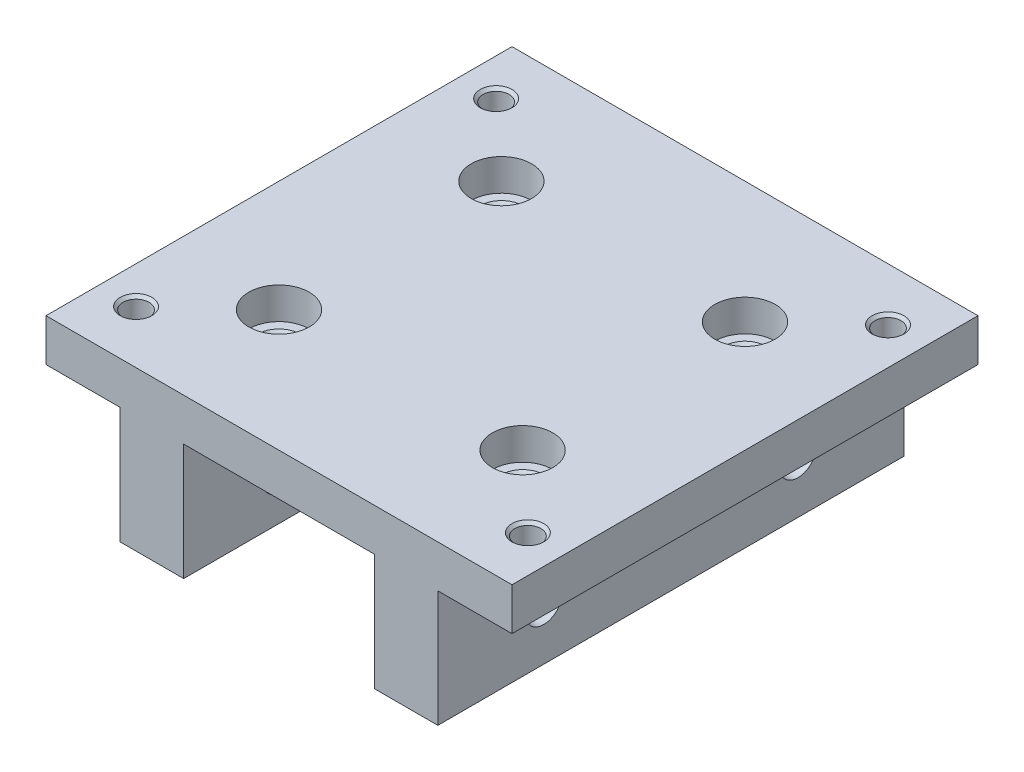
SolidWorks part; units mm, degrees
ref_plane "Front Plane" through (0, 0, 0) normal (0, 0, 1) x (1, 0, 0)
ref_plane "Top Plane" through (0, 0, 0) normal (0, 1, 0) x (1, 0, 0)
ref_plane "Right Plane" through (0, 0, 0) normal (1, 0, 0) x (0, 0, -1)
ref_plane "Plane1" through (0, 0, 0) normal (0, 0, 1) x (1, 0, 0)
sketch "Sketch1" plane through (0, 0, 0) normal (0, 0, 1) x (1, 0, 0)
  line L0 (-22, 15) -> (-22, 11)
  line L1 (-22, 11) -> (-15, 11)
  line L2 (-15, 11) -> (-15, 0)
  line L3 (-15, 0) -> (-9, 0)
  line L4 (-9, 0) -> (-9, 11)
  line L5 (-9, 11) -> (9, 11)
  line L6 (9, 11) -> (9, 0)
  line L7 (9, 0) -> (15, 0)
  line L8 (15, 0) -> (15, 11)
  line L9 (15, 11) -> (22, 11)
  line L10 (22, 11) -> (22, 15)
  line L11 (22, 15) -> (-22, 15)
extrude "Boss-Extrude1" add sketch "Sketch1" along normal blind 44
ref_plane "Plane2" through (0, 0, 5) normal (0, 0, 1) x (1, 0, 0)
sketch "Sketch2" plane through (0, 0, 5) normal (0, 0, 1) x (1, 0, 0)
  line L0 (18.5, 15) -> (20, 15)
  line L1 (20, 15) -> (19.7295, 14.7295)
  line L2 (19.7295, 14.7295) -> (19.7295, 11.2705)
  line L3 (19.7295, 11.2705) -> (20, 11)
  line L4 (20, 11) -> (18.5, 11)
  line L5 (18.5, 11) -> (18.5, 15)
  line L6 (18.5, 11) -> (18.5, 15) construction
revolve "Cut-Revolve1" cut sketch "Sketch2" angle 360 about L6
ref_plane "Plane3" through (0, 0, 39) normal (0, 0, 1) x (1, 0, 0)
sketch "Sketch3" plane through (0, 0, 39) normal (0, 0, 1) x (1, 0, 0)
  line L0 (18.5, 15) -> (20, 15)
  line L1 (20, 15) -> (19.7295, 14.7295)
  line L2 (19.7295, 14.7295) -> (19.7295, 11.2705)
  line L3 (19.7295, 11.2705) -> (20, 11)
  line L4 (20, 11) -> (18.5, 11)
  line L5 (18.5, 11) -> (18.5, 15)
  line L6 (18.5, 11) -> (18.5, 15) construction
revolve "Cut-Revolve2" cut sketch "Sketch3" angle 360 about L6
ref_plane "Plane4" through (0, 0, 10) normal (0, 0, 1) x (1, 0, 0)
sketch "Sketch4" plane through (0, 0, 10) normal (0, 0, 1) x (1, 0, 0)
  line L0 (-10.07, 1.95) -> (-10.07, 8.05)
  line L1 (-10.07, -50) -> (-10.07, 50) construction
  arc A0 (-10.07, 8.05) -> (-10.07, 1.95) centre (-10.07, 5) cw
revolve "Revolve1" add sketch "Sketch4" angle 360 about L1
ref_plane "Plane5" through (0, 0, 34) normal (0, 0, 1) x (1, 0, 0)
sketch "Sketch5" plane through (0, 0, 34) normal (0, 0, 1) x (1, 0, 0)
  line L0 (-10.07, 1.95) -> (-10.07, 8.05)
  line L1 (-10.07, -50) -> (-10.07, 50) construction
  arc A0 (-10.07, 8.05) -> (-10.07, 1.95) centre (-10.07, 5) cw
revolve "Revolve2" add sketch "Sketch5" angle 360 about L1
ref_plane "Plane6" through (0, 0, 34) normal (0, 0, 1) x (1, 0, 0)
sketch "Sketch6" plane through (0, 0, 34) normal (0, 0, 1) x (1, 0, 0)
  line L0 (10.07, 8.05) -> (10.07, 1.95)
  line L1 (10.07, 50) -> (10.07, -50) construction
  arc A0 (10.07, 1.95) -> (10.07, 8.05) centre (10.07, 5) cw
revolve "Revolve3" add sketch "Sketch6" angle 360 about L1
ref_plane "Plane7" through (0, 0, 10) normal (0, 0, 1) x (1, 0, 0)
sketch "Sketch7" plane through (0, 0, 10) normal (0, 0, 1) x (1, 0, 0)
  line L0 (10.07, 8.05) -> (10.07, 1.95)
  line L1 (10.07, 50) -> (10.07, -50) construction
  arc A0 (10.07, 1.95) -> (10.07, 8.05) centre (10.07, 5) cw
revolve "Revolve4" add sketch "Sketch7" angle 360 about L1
ref_plane "Plane8" through (20.5, 0, 0) normal (1, 0, 0) x (0, 0, -1)
sketch "Sketch8" plane through (20.5, 0, 0) normal (1, 0, 0) x (0, 0, -1)
  circle A0 centre (-10, 5) radius 1.75
extrude "Cut-Extrude1" cut sketch "Sketch8" against normal blind 7
ref_plane "Plane9" through (20.5, 0, 0) normal (1, 0, 0) x (0, 0, -1)
sketch "Sketch9" plane through (20.5, 0, 0) normal (1, 0, 0) x (0, 0, -1)
  circle A0 centre (-34, 5) radius 1.75
extrude "Cut-Extrude2" cut sketch "Sketch9" against normal blind 7
ref_plane "Plane10" through (-20.5, 0, 0) normal (1, 0, 0) x (0, 0, -1)
sketch "Sketch10" plane through (-20.5, 0, 0) normal (1, 0, 0) x (0, 0, -1)
  circle A0 centre (-10, 5) radius 1.75
extrude "Cut-Extrude3" cut sketch "Sketch10" along normal blind 7
ref_plane "Plane11" through (-20.5, 0, 0) normal (1, 0, 0) x (0, 0, -1)
sketch "Sketch11" plane through (-20.5, 0, 0) normal (1, 0, 0) x (0, 0, -1)
  circle A0 centre (-34, 5) radius 1.75
extrude "Cut-Extrude4" cut sketch "Sketch11" along normal blind 7
ref_plane "Plane12" through (0, 0, 5) normal (0, 0, 1) x (1, 0, 0)
sketch "Sketch12" plane through (0, 0, 5) normal (0, 0, 1) x (1, 0, 0)
  line L0 (-18.5, 15) -> (-17, 15)
  line L1 (-17, 15) -> (-17.2705, 14.7295)
  line L2 (-17.2705, 14.7295) -> (-17.2705, 11.2705)
  line L3 (-17.2705, 11.2705) -> (-17, 11)
  line L4 (-17, 11) -> (-18.5, 11)
  line L5 (-18.5, 11) -> (-18.5, 15)
  line L6 (-18.5, 11) -> (-18.5, 15) construction
revolve "Cut-Revolve3" cut sketch "Sketch12" angle 360 about L6
ref_plane "Plane13" through (0, 0, 39) normal (0, 0, 1) x (1, 0, 0)
sketch "Sketch13" plane through (0, 0, 39) normal (0, 0, 1) x (1, 0, 0)
  line L0 (-18.5, 15) -> (-17, 15)
  line L1 (-17, 15) -> (-17.2705, 14.7295)
  line L2 (-17.2705, 14.7295) -> (-17.2705, 11.2705)
  line L3 (-17.2705, 11.2705) -> (-17, 11)
  line L4 (-17, 11) -> (-18.5, 11)
  line L5 (-18.5, 11) -> (-18.5, 15)
  line L6 (-18.5, 11) -> (-18.5, 15) construction
revolve "Cut-Revolve4" cut sketch "Sketch13" angle 360 about L6
ref_plane "Plane14" through (11.5, 0, 0) normal (1, 0, 0) x (0, 0, -1)
sketch "Sketch14" plane through (11.5, 0, 0) normal (1, 0, 0) x (0, 0, -1)
  line L0 (-11.5, 3.8641) -> (-13.121, 4.8)
  line L1 (-13.121, 4.8) -> (-13.121, 11.621)
  line L2 (-13.121, 11.621) -> (-13.5, 12)
  line L3 (-13.5, 12) -> (-14.35, 12)
  line L4 (-14.35, 12) -> (-14.35, 15)
  line L5 (-14.35, 15) -> (-11.5, 15)
  line L6 (-11.5, 15) -> (-11.5, 3.8641)
  line L7 (-11.5, 15) -> (-11.5, 3.8641) construction
revolve "Cut-Revolve5" cut sketch "Sketch14" angle 360 about L7
ref_plane "Plane15" through (11.5, 0, 0) normal (1, 0, 0) x (0, 0, -1)
sketch "Sketch15" plane through (11.5, 0, 0) normal (1, 0, 0) x (0, 0, -1)
  line L0 (-32.5, 15) -> (-29.65, 15)
  line L1 (-29.65, 15) -> (-29.65, 12)
  line L2 (-29.65, 12) -> (-30.5, 12)
  line L3 (-30.5, 12) -> (-30.879, 11.621)
  line L4 (-30.879, 11.621) -> (-30.879, 4.8)
  line L5 (-30.879, 4.8) -> (-32.5, 3.8641)
  line L6 (-32.5, 3.8641) -> (-32.5, 15)
  line L7 (-32.5, 3.8641) -> (-32.5, 15) construction
revolve "Cut-Revolve6" cut sketch "Sketch15" angle 360 about L7
ref_plane "Plane16" through (-11.5, 0, 0) normal (1, 0, 0) x (0, 0, -1)
sketch "Sketch16" plane through (-11.5, 0, 0) normal (1, 0, 0) x (0, 0, -1)
  line L0 (-11.5, 3.8641) -> (-13.121, 4.8)
  line L1 (-13.121, 4.8) -> (-13.121, 11.621)
  line L2 (-13.121, 11.621) -> (-13.5, 12)
  line L3 (-13.5, 12) -> (-14.35, 12)
  line L4 (-14.35, 12) -> (-14.35, 15)
  line L5 (-14.35, 15) -> (-11.5, 15)
  line L6 (-11.5, 15) -> (-11.5, 3.8641)
  line L7 (-11.5, 15) -> (-11.5, 3.8641) construction
revolve "Cut-Revolve7" cut sketch "Sketch16" angle 360 about L7
ref_plane "Plane17" through (-11.5, 0, 0) normal (1, 0, 0) x (0, 0, -1)
sketch "Sketch17" plane through (-11.5, 0, 0) normal (1, 0, 0) x (0, 0, -1)
  line L0 (-32.5, 15) -> (-29.65, 15)
  line L1 (-29.65, 15) -> (-29.65, 12)
  line L2 (-29.65, 12) -> (-30.5, 12)
  line L3 (-30.5, 12) -> (-30.879, 11.621)
  line L4 (-30.879, 11.621) -> (-30.879, 4.8)
  line L5 (-30.879, 4.8) -> (-32.5, 3.8641)
  line L6 (-32.5, 3.8641) -> (-32.5, 15)
  line L7 (-32.5, 3.8641) -> (-32.5, 15) construction
revolve "Cut-Revolve8" cut sketch "Sketch17" angle 360 about L7
